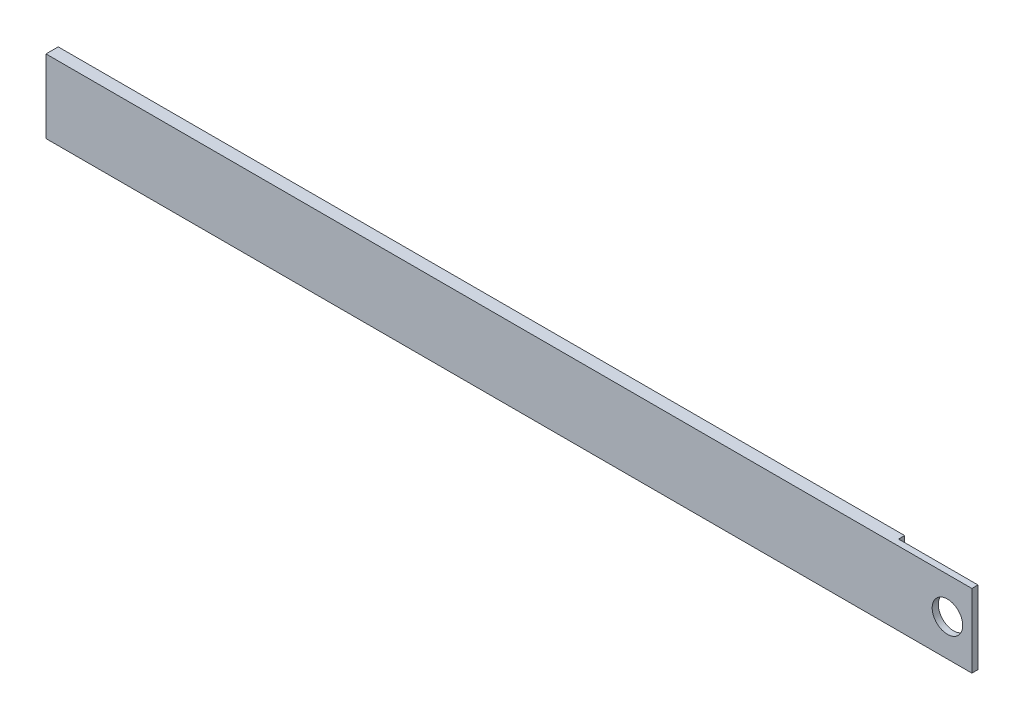
SolidWorks part; units mm, degrees
ref_plane "Alzado" through (0, 0, 0) normal (0, 0, 1) x (1, 0, 0)
ref_plane "Planta" through (0, 0, 0) normal (0, 1, 0) x (1, 0, 0)
ref_plane "Vista lateral" through (0, 0, 0) normal (1, 0, 0) x (0, 0, -1)
sketch "Croquis1" plane through (0, 0, 0) normal (0, 1, 0) x (1, 0, 0)
  line L1 (-65.8443, 24.0382) -> (83.1557, 24.0382)
  line L3 (-65.8443, 26.0382) -> (83.1557, 26.0382)
  line L4 (83.1557, 24.0382) -> (83.1557, 26.0382)
  line L8 (-65.8443, 26.0382) -> (-68.3443, 26.0382)
  line L9 (-68.3443, 26.0382) -> (-68.3443, 24.0382)
  line L10 (-68.3443, 24.0382) -> (-65.8443, 24.0382)
  dimension "D1" = 149
  dimension "D2" = 2.5
  dimension "D3" = 2.5
  dimension "D6" = 2
extrude "Saliente-Extruir1" add sketch "Croquis1" along normal blind 12
sketch "Croquis4" plane through (0, 0, -24.0382) normal (0, 0, 1) x (1, 0, 0)
  line L0 (83.1557, 12) -> (83.1557, 0) construction
  line L1 (-68.3443, 12) -> (83.1557, 12) construction
  circle A0 centre (79.1557, 6) radius 2.5
  dimension "D2" = 5
  dimension "D1" = 4
  dimension "D3" = 6
extrude "Cortar-Extruir1" cut sketch "Croquis4" against normal blind 1
sketch "Croquis5" plane through (0, 0, -25.0382) normal (0, 0, 1) x (1, 0, 0)
  line L0 (83.1557, 12) -> (83.1557, 0) construction
  line L1 (-68.3443, 12) -> (83.1557, 12) construction
  circle A0 centre (79.1557, 6) radius 1.5
  dimension "D1" = 3
  dimension "D2" = 4
  dimension "D3" = 6
extrude "Cortar-Extruir2" cut sketch "Croquis5" against normal blind 1
sketch "Croquis6" plane through (0, 12, 0) normal (0, 1, 0) x (1, 0, 0)
  line L0 (83.1557, 24.0382) -> (83.1557, 26.0382) construction
  line L1 (83.1557, 25.0382) -> (70.1557, 25.0382)
  line L2 (83.1557, 25.0382) -> (83.1557, 26.0382)
  line L3 (83.1557, 26.0382) -> (70.1557, 26.0382)
  line L4 (70.1557, 25.0382) -> (70.1557, 26.0382)
  line L5 (83.1557, 26.0382) -> (-68.3443, 26.0382) construction
  dimension "D1" = 1
  dimension "D2" = 13
extrude "Cortar-Extruir3" cut sketch "Croquis6" against normal blind 12
